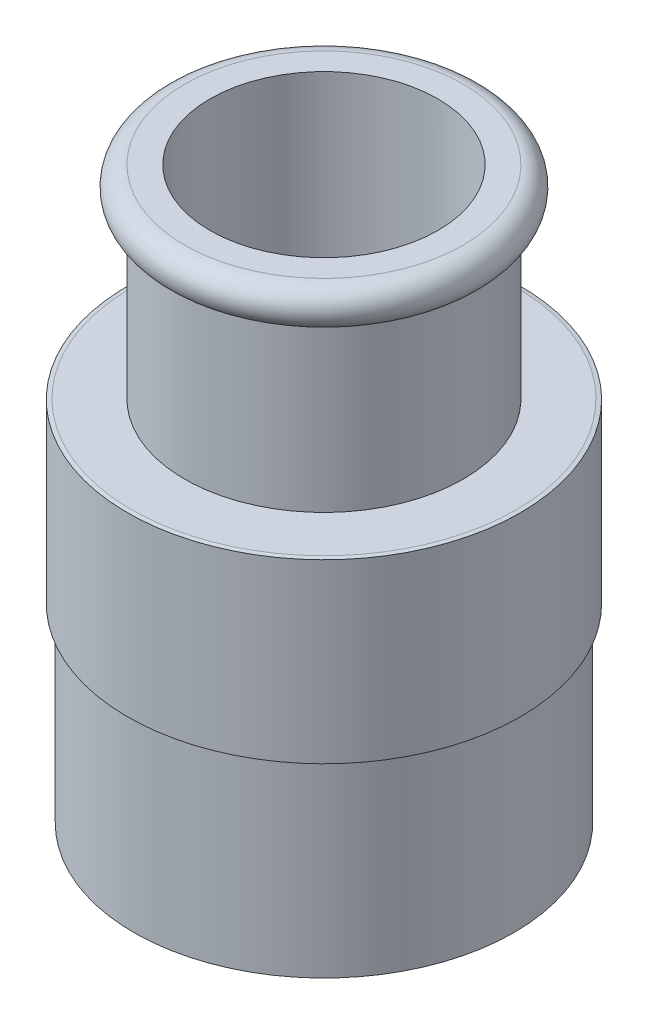
SolidWorks part; units mm, degrees
ref_plane "Alzado" through (0, 0, 0) normal (0, 0, 1) x (1, 0, 0)
ref_plane "Planta" through (0, 0, 0) normal (0, 1, 0) x (1, 0, 0)
ref_plane "Vista lateral" through (0, 0, 0) normal (1, 0, 0) x (0, 0, -1)
sketch "Croquis1" plane through (0, 0, 0) normal (0, 0, 1) x (1, 0, 0)
  line L0 (7.4338, -7) -> (7.75, -7.0513)
  line L1 (7.75, -9) -> (1.25, -9)
  line L2 (7.75, -9) -> (7.75, 9) construction
  line L3 (7.75, 9) -> (-7.75, 9) construction
  line L4 (-7.75, -9) -> (-7.75, 9) construction
  line L5 (7.75, -9) -> (-7.75, 9) construction
  line L6 (7.75, 9) -> (-7.75, -9) construction
  line L7 (1.25, -9) -> (7.75, -9)
  line L8 (-7.75, -9) -> (-7.75, -7)
  line L10 (7.75, -9) -> (7.75, -7.0513)
  line L11 (3.25, -7) -> (7.4338, -7)
  line L12 (1.25, -9) -> (4.7653, -9)
  line L13 (-7.75, -7) -> (-7.75, 9)
  line L14 (1.25, 9) -> (3.25, 9)
  line L15 (3.25, -7) -> (3.25, 6)
  line L16 (7.75, -9) -> (1.25, -9)
  line L17 (7.75, -9) -> (7.75, -21)
  line L18 (-7.75, 9) -> (-7.75, -9)
  line L19 (-7.75, -9) -> (1.25, -9)
  line L20 (1.25, 9) -> (1.25, -9)
  line L21 (7.75, -21) -> (1.25, -21)
  line L22 (1.25, -9) -> (1.25, -21)
  line L23 (1.25, -21) -> (7.25, -21)
  line L24 (1.25, -21) -> (1.25, -36)
  line L25 (1.25, -36) -> (7.25, -36)
  line L26 (7.25, -21) -> (7.25, -36)
  arc A0 (3.25, 9) -> (3.25, 6) centre (3.25, 7.5) cw
  point P0 (0, 0)
  point P6 (7.75, -6.0513)
  dimension "D5" = 1.5
  dimension "D1" = 15.5
  dimension "D2" = 18
  dimension "D3" = 2
  dimension "D4" = 11
  dimension "D7" = 9
  dimension "D8" = 12
  dimension "D9" = 6
  dimension "D10" = 15
  dimension "D11" = 2
revolve "Revolución1" add sketch "Croquis1" angle 360 about L13
sketch "Croquis2" plane through (0, 0, 0) normal (0, 0, 1) x (1, 0, 0)
  line L0 (-23.25, -14.0257) -> (7.75, -14.0257) construction
  line L1 (-23.25, -7.0513) -> (-23.25, -21) construction
  line L2 (7.75, -21) -> (7.75, -7.0513) construction
  circle A0 centre (-7.75, -14.0257) radius 4.4162
extrude "Cortar-Extruir1" cut sketch "Croquis2" against normal through all
